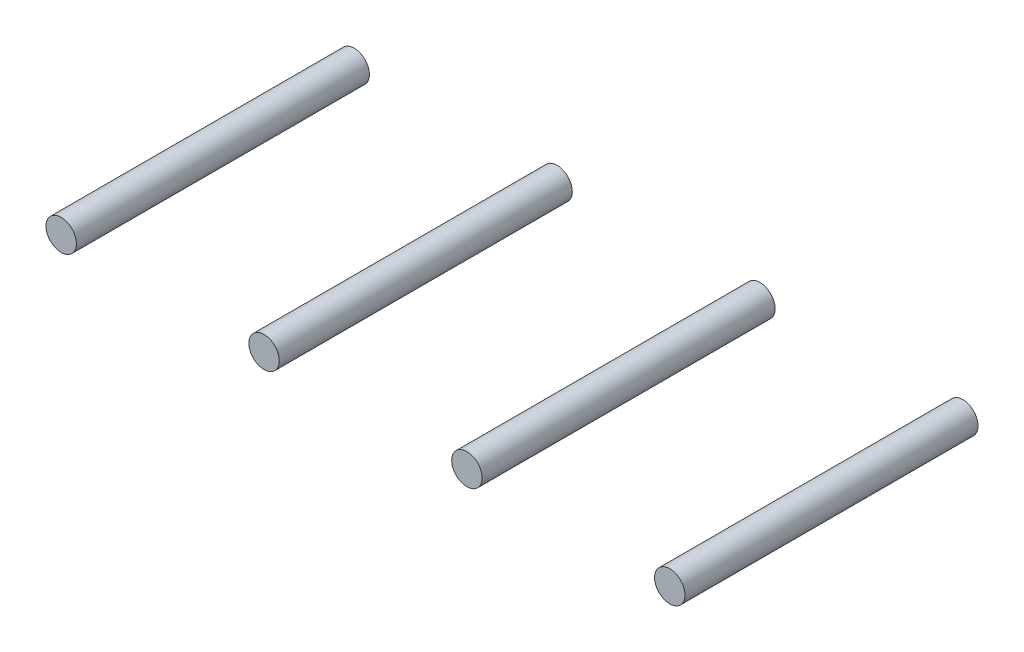
SolidWorks part; units mm, degrees
ref_plane "Front Plane" through (0, 0, 0) normal (0, 0, 1) x (1, 0, 0)
ref_plane "Top Plane" through (0, 0, 0) normal (0, 1, 0) x (1, 0, 0)
ref_plane "Right Plane" through (0, 0, 0) normal (1, 0, 0) x (0, 0, -1)
sketch "Sketch1" plane through (0, 0, 0) normal (0, 0, 1) x (1, 0, 0)
  line L0 (0, 0) -> (-28.4177, 0) construction
  line L1 (0, 0) -> (0, -28.4927) construction
  circle A0 centre (-27, -35) radius 1.35
  circle A1 centre (-9, -35) radius 1.35
  circle A2 centre (27, -35) radius 1.35
  circle A3 centre (9, -35) radius 1.35
  dimension "D1" = 2.7
  dimension "D2" = 35
  dimension "D3" = 54
  dimension "D4" = 18
extrude "Boss-Extrude1" add sketch "Sketch1" along normal blind 10 and the other way up to surface (16 mm away)
